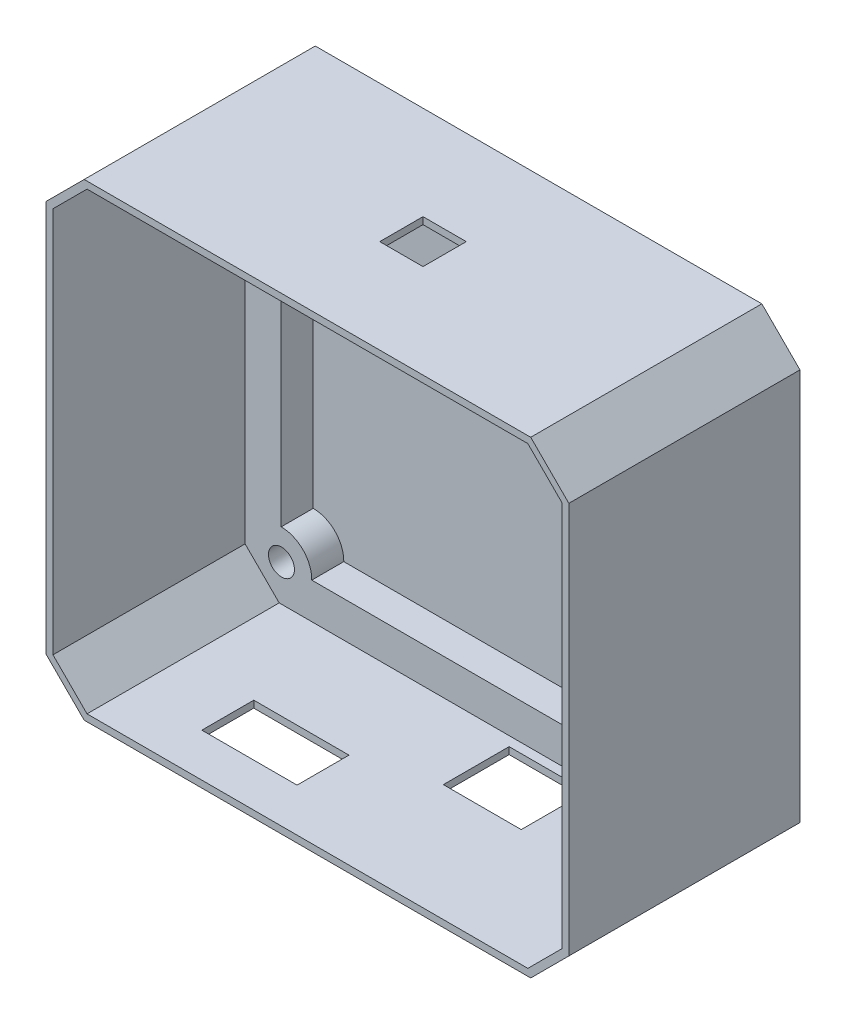
SolidWorks part; units mm, degrees
ref_plane "前基準面" through (0, 0, 0) normal (0, 0, 1) x (1, 0, 0)
ref_plane "上基準面" through (0, 0, 0) normal (0, 1, 0) x (1, 0, 0)
ref_plane "右基準面" through (0, 0, 0) normal (1, 0, 0) x (0, 0, -1)
sketch "草圖1" plane through (0, 0, 0) normal (0, 0, 1) x (1, 0, 0)
  line L0 (-29.2, 22.23) -> (-25.38, 26.05) construction
  line L1 (-29.2, 26.05) -> (29.2, 26.05) construction
  line L2 (-29.2, 26.05) -> (-29.2, -26.05) construction
  line L3 (-29.2, -26.05) -> (29.2, -26.05) construction
  line L4 (29.2, 26.05) -> (29.2, -26.05) construction
  line L5 (0, 26.05) -> (0, -26.05) construction
  line L6 (-29.2, 0) -> (29.2, 0) construction
  line L7 (-29.4, 22.3128) -> (-25.4628, 26.25)
  line L8 (-29.3414, 22.3714) -> (-25.5214, 26.1914) construction
  line L9 (29.4, 22.3128) -> (25.4628, 26.25)
  line L10 (-29.4, 22.3128) -> (-29.4, -22.3128)
  line L11 (-25.4628, -26.25) -> (25.4628, -26.25)
  line L12 (29.4, 22.3128) -> (29.4, -22.3128)
  line L13 (-25.4628, 26.25) -> (25.4628, 26.25)
  line L14 (29.4, -22.3128) -> (25.4628, -26.25)
  line L15 (-29.4, -22.3128) -> (-25.4628, -26.25)
  line L16 (-25.7942, 27.05) -> (25.7942, 27.05)
  line L17 (-29.4, 26.25) -> (29.4, 26.25) construction
  line L18 (-29.4, 26.25) -> (-29.4, -26.25) construction
  line L19 (-29.4, -26.25) -> (29.4, -26.25) construction
  line L20 (29.4, 26.25) -> (29.4, -26.25) construction
  line L21 (30.2, 22.6442) -> (25.7942, 27.05)
  line L22 (30.2, 22.6442) -> (30.2, -22.6442)
  line L23 (30.2, -22.6442) -> (25.7942, -27.05)
  line L24 (-25.7942, -27.05) -> (25.7942, -27.05)
  line L25 (-30.2, -22.6442) -> (-25.7942, -27.05)
  line L26 (-30.2, 22.6442) -> (-30.2, -22.6442)
  line L27 (-30.2, 22.6442) -> (-25.7942, 27.05)
  point P4 (0, 26.05)
  point P6 (-29.2, 0)
  dimension "D1" = 58.4
  dimension "D2" = 52.1
  dimension "D5" = 5.4023
  dimension "D6" = 0.2
  dimension "D7" = 0.2
  dimension "D8" = 0.8
  dimension "D3" = 3.82
  dimension "D4" = 3.82
extrude "填料-伸長1" add sketch "草圖1" along normal blind 22.2
sketch "草圖2" plane through (0, 0, 0) normal (0, 0, -1) x (-1, 0, 0)
  line L0 (-30.2, 22.6442) -> (-25.7942, 27.05)
  line L1 (-25.7942, 27.05) -> (25.7942, 27.05)
  line L2 (25.7942, 27.05) -> (30.2, 22.6442)
  line L3 (30.2, 22.6442) -> (30.2, -22.6442)
  line L4 (30.2, -22.6442) -> (25.7942, -27.05)
  line L5 (25.7942, -27.05) -> (-25.7942, -27.05)
  line L6 (-25.7942, -27.05) -> (-30.2, -22.6442)
  line L7 (-30.2, -22.6442) -> (-30.2, 22.6442)
extrude "填料-伸長2" add sketch "草圖2" along normal blind 4.5
sketch "草圖3" plane through (0, 0, 0) normal (0, 0, 1) x (1, 0, 0)
  line L2 (-30.2, 0) -> (30.2, 0) construction
  line L5 (0, 27.05) -> (0, -27.05) construction
  line L8 (25.7942, 27.05) -> (-25.7942, 27.05) construction
  line L9 (-25.7942, -27.05) -> (25.7942, -27.05) construction
  line L10 (30.2, -22.6442) -> (30.2, 22.6442) construction
  line L11 (-30.2, 22.6442) -> (-30.2, -22.6442) construction
  circle A0 centre (25.2, 22.03) radius 1.5
  circle A1 centre (25.2, -22.03) radius 1.5
  circle A2 centre (-25.2, -22.03) radius 1.5
  circle A3 centre (-25.2, 22.03) radius 1.5
  dimension "D1" = 3
  dimension "D2" = 5.02
  dimension "D3" = 5
extrude "除料-伸長1" cut sketch "草圖3" against normal through all
sketch "草圖5" plane through (0, 0, 0) normal (0, 0, 1) x (1, 0, 0)
  line L0 (-25.2341, 18.5302) -> (-25.2341, -18.5302)
  line L1 (-21.7005, -22.0917) -> (21.7005, -22.0917)
  line L2 (25.2974, -18.5314) -> (25.2974, 18.5314)
  line L3 (21.7461, 22.5961) -> (-21.7461, 22.5961)
  arc A0 (-25.2341, 18.5302) -> (-21.7461, 22.5961) centre (-25.2, 22.03) ccw
  arc A2 (21.7461, 22.5961) -> (25.2974, 18.5314) centre (25.2, 22.03) ccw
  arc A3 (25.2974, -18.5314) -> (21.7005, -22.0917) centre (25.2, -22.03) ccw
  arc A4 (-21.7005, -22.0917) -> (-25.2341, -18.5302) centre (-25.2, -22.03) ccw
  point P9 (22.5643, 19.7272)
  point P30 (22.7378, -19.5426)
  point P31 (-22.5435, 19.7511)
  point P32 (-22.7154, -19.5649)
  dimension "D1" = 7
  dimension "D2" = 3.5
  dimension "D3" = 7
  dimension "D4" = 7
  dimension "D5" = 7
  dimension "D6" = 3.5
  dimension "D7" = 3.5
  dimension "D8" = 3.5
extrude "除料-伸長3" cut sketch "草圖5" against normal blind 3.7
sketch "草圖6" plane through (0, -27.05, 0) normal (0, -1, 0) x (1, 0, 0)
  line L0 (30.2, 22.2) -> (30.2, -4.5) construction
  line L1 (2.2, 8.7) -> (11.2, 8.7)
  line L2 (2.2, 8.7) -> (2.2, 1.1)
  line L3 (2.2, 1.1) -> (11.2, 1.1)
  line L4 (11.2, 8.7) -> (11.2, 1.1)
  line L5 (-17.2, 17.2) -> (-6.2, 17.2)
  line L6 (-17.2, 17.2) -> (-17.2, 11.2)
  line L7 (-17.2, 11.2) -> (-6.2, 11.2)
  line L8 (-6.2, 17.2) -> (-6.2, 11.2)
  line L9 (25.7942, -4.5) -> (-25.7942, -4.5) construction
  line L10 (-25.7942, 22.2) -> (25.7942, 22.2) construction
  line L11 (-30.2, 22.2) -> (-30.2, -4.5) construction
  dimension "D1" = 28
  dimension "D2" = 9
  dimension "D3" = 7.6
  dimension "D4" = 5.6
  dimension "D5" = 5
  dimension "D6" = 6
  dimension "D7" = 13
  dimension "D8" = 11
extrude "除料-伸長4" cut sketch "草圖6" against normal up to next
sketch "草圖7" plane through (0, 27.05, 0) normal (0, 1, 0) x (1, 0, 0)
  line L0 (30.2, -22.2) -> (30.2, 4.5) construction
  line L1 (2.5, -11.35) -> (-2.5, -11.35)
  line L2 (2.5, -11.35) -> (2.5, -6.35)
  line L3 (2.5, -6.35) -> (-2.5, -6.35)
  line L4 (-2.5, -11.35) -> (-2.5, -6.35)
  point P4 (0, -11.35)
  point P8 (30.2, -8.85)
  point P9 (2.5, -8.85)
  dimension "D1" = 5
  dimension "D2" = 5
extrude "除料-伸長5" cut sketch "草圖7" against normal up to next
